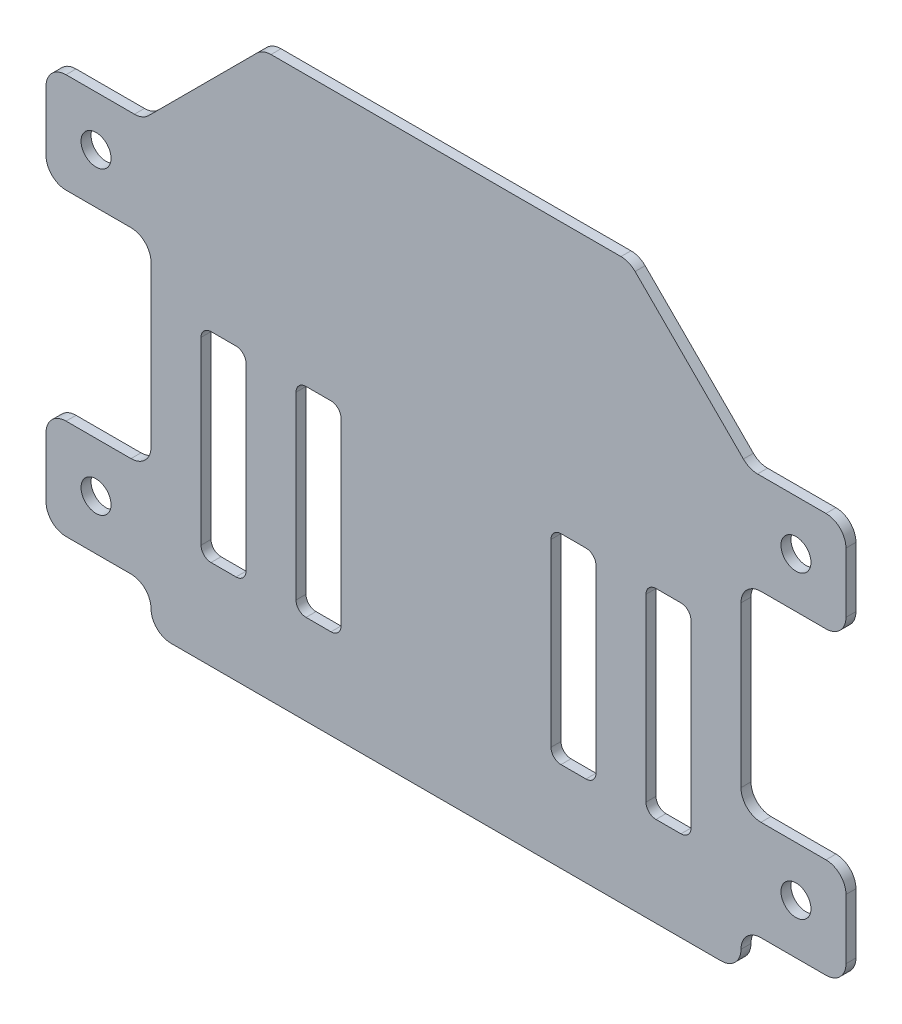
SolidWorks part; units mm, degrees
ref_plane "Спереди" through (0, 0, 0) normal (0, 0, 1) x (1, 0, 0)
ref_plane "Сверху" through (0, 0, 0) normal (0, 1, 0) x (1, 0, 0)
ref_plane "Справа" through (0, 0, 0) normal (1, 0, 0) x (0, 0, -1)
sketch "Model" plane through (0, 0, 0) normal (0, 0, 1) x (1, 0, 0)
  line L0 (-23.5, 9) -> (-21, 9)
  line L1 (-23.5, 29) -> (-21, 29)
  line L2 (-20, 28) -> (-20, 10)
  line L3 (-24.5, 10) -> (-24.5, 28)
  line L4 (-29.5, 16) -> (-29.5, 32)
  line L5 (-18.9142, 55.4142) -> (-29.7426, 44.5858)
  line L6 (-17.5, 56) -> (0, 56)
  line L7 (-38, 4) -> (-31.5, 4)
  line L8 (-38, 14) -> (-31.5, 14)
  line L9 (-40, 6) -> (-40, 12)
  line L10 (-14, 9) -> (-11.5, 9)
  line L11 (-14, 29) -> (-11.5, 29)
  line L12 (-10.5, 28) -> (-10.5, 10)
  line L13 (-15, 10) -> (-15, 28)
  line L14 (-38, 44) -> (-31.1569, 44)
  line L15 (-38, 34) -> (-31.5, 34)
  line L16 (-40, 42) -> (-40, 36)
  line L17 (-27.5, 0) -> (0, 0)
  line L18 (23.5, 9) -> (21, 9)
  line L19 (23.5, 29) -> (21, 29)
  line L20 (20, 28) -> (20, 10)
  line L21 (24.5, 10) -> (24.5, 28)
  line L22 (29.5, 16) -> (29.5, 32)
  line L23 (18.9142, 55.4142) -> (29.7426, 44.5858)
  line L24 (17.5, 56) -> (0, 56)
  line L25 (38, 4) -> (31.5, 4)
  line L26 (38, 14) -> (31.5, 14)
  line L27 (40, 6) -> (40, 12)
  line L28 (14, 9) -> (11.5, 9)
  line L29 (14, 29) -> (11.5, 29)
  line L30 (10.5, 28) -> (10.5, 10)
  line L31 (15, 10) -> (15, 28)
  line L32 (38, 44) -> (31.1569, 44)
  line L33 (38, 34) -> (31.5, 34)
  line L34 (40, 42) -> (40, 36)
  line L35 (27.5, 0) -> (0, 0)
  line L36 (23.5, 9) -> (21, 9)
  line L37 (23.5, 29) -> (21, 29)
  line L38 (20, 28) -> (20, 10)
  line L39 (24.5, 10) -> (24.5, 28)
  line L40 (29.5, 16) -> (29.5, 32)
  line L41 (18.9142, 55.4142) -> (29.7426, 44.5858)
  line L42 (17.5, 56) -> (0, 56)
  line L43 (38, 4) -> (31.5, 4)
  line L44 (38, 14) -> (31.5, 14)
  line L45 (40, 6) -> (40, 12)
  line L46 (14, 9) -> (11.5, 9)
  line L47 (14, 29) -> (11.5, 29)
  line L48 (10.5, 28) -> (10.5, 10)
  line L49 (15, 10) -> (15, 28)
  line L50 (38, 44) -> (31.1569, 44)
  line L51 (38, 34) -> (31.5, 34)
  line L52 (40, 42) -> (40, 36)
  line L53 (27.5, 0) -> (0, 0)
  circle A0 centre (-35, 9) radius 1.5
  arc A1 (-24.5, 10) -> (-23.5, 9) centre (-23.5, 10) ccw
  arc A2 (-21, 9) -> (-20, 10) centre (-21, 10) ccw
  arc A3 (-23.5, 29) -> (-24.5, 28) centre (-23.5, 28) ccw
  arc A4 (-20, 28) -> (-21, 29) centre (-21, 28) ccw
  circle A5 centre (-35, 9) radius 1.5
  arc A6 (-38, 14) -> (-40, 12) centre (-38, 12) ccw
  arc A7 (-40, 6) -> (-38, 4) centre (-38, 6) ccw
  arc A8 (-29.5, 2) -> (-31.5, 4) centre (-31.5, 2) ccw
  arc A9 (-31.5, 14) -> (-29.5, 16) centre (-31.5, 16) ccw
  arc A10 (-15, 10) -> (-14, 9) centre (-14, 10) ccw
  arc A11 (-11.5, 9) -> (-10.5, 10) centre (-11.5, 10) ccw
  arc A12 (-14, 29) -> (-15, 28) centre (-14, 28) ccw
  arc A13 (-10.5, 28) -> (-11.5, 29) centre (-11.5, 28) ccw
  circle A14 centre (-35, 39) radius 1.5
  circle A15 centre (-35, 39) radius 1.5
  arc A16 (-40, 36) -> (-38, 34) centre (-38, 36) ccw
  arc A17 (-38, 44) -> (-40, 42) centre (-38, 42) ccw
  arc A18 (-29.5, 32) -> (-31.5, 34) centre (-31.5, 32) ccw
  arc A19 (-29.5, 2) -> (-27.5, 0) centre (-27.5, 2) ccw
  arc A20 (-31.1569, 44) -> (-29.7426, 44.5858) centre (-31.1569, 46) ccw
  arc A21 (-17.5, 56) -> (-18.9142, 55.4142) centre (-17.5, 54) ccw
  circle A22 centre (35, 9) radius 1.5
  arc A23 (23.5, 9) -> (24.5, 10) centre (23.5, 10) ccw
  arc A24 (20, 10) -> (21, 9) centre (21, 10) ccw
  arc A25 (24.5, 28) -> (23.5, 29) centre (23.5, 28) ccw
  arc A26 (21, 29) -> (20, 28) centre (21, 28) ccw
  circle A27 centre (35, 9) radius 1.5
  arc A28 (40, 12) -> (38, 14) centre (38, 12) ccw
  arc A29 (38, 4) -> (40, 6) centre (38, 6) ccw
  arc A30 (31.5, 4) -> (29.5, 2) centre (31.5, 2) ccw
  arc A31 (29.5, 16) -> (31.5, 14) centre (31.5, 16) ccw
  arc A32 (14, 9) -> (15, 10) centre (14, 10) ccw
  arc A33 (10.5, 10) -> (11.5, 9) centre (11.5, 10) ccw
  arc A34 (15, 28) -> (14, 29) centre (14, 28) ccw
  arc A35 (11.5, 29) -> (10.5, 28) centre (11.5, 28) ccw
  circle A36 centre (35, 39) radius 1.5
  circle A37 centre (35, 39) radius 1.5
  arc A38 (38, 34) -> (40, 36) centre (38, 36) ccw
  arc A39 (40, 42) -> (38, 44) centre (38, 42) ccw
  arc A40 (31.5, 34) -> (29.5, 32) centre (31.5, 32) ccw
  arc A41 (27.5, 0) -> (29.5, 2) centre (27.5, 2) ccw
  arc A42 (29.7426, 44.5858) -> (31.1569, 44) centre (31.1569, 46) ccw
  arc A43 (18.9142, 55.4142) -> (17.5, 56) centre (17.5, 54) ccw
  circle A44 centre (35, 9) radius 1.5
  arc A45 (23.5, 9) -> (24.5, 10) centre (23.5, 10) ccw
  arc A46 (20, 10) -> (21, 9) centre (21, 10) ccw
  arc A47 (24.5, 28) -> (23.5, 29) centre (23.5, 28) ccw
  arc A48 (21, 29) -> (20, 28) centre (21, 28) ccw
  circle A49 centre (35, 9) radius 1.5
  arc A50 (40, 12) -> (38, 14) centre (38, 12) ccw
  arc A51 (38, 4) -> (40, 6) centre (38, 6) ccw
  arc A52 (31.5, 4) -> (29.5, 2) centre (31.5, 2) ccw
  arc A53 (29.5, 16) -> (31.5, 14) centre (31.5, 16) ccw
  arc A54 (14, 9) -> (15, 10) centre (14, 10) ccw
  arc A55 (10.5, 10) -> (11.5, 9) centre (11.5, 10) ccw
  arc A56 (15, 28) -> (14, 29) centre (14, 28) ccw
  arc A57 (11.5, 29) -> (10.5, 28) centre (11.5, 28) ccw
  circle A58 centre (35, 39) radius 1.5
  circle A59 centre (35, 39) radius 1.5
  arc A60 (38, 34) -> (40, 36) centre (38, 36) ccw
  arc A61 (40, 42) -> (38, 44) centre (38, 42) ccw
  arc A62 (31.5, 34) -> (29.5, 32) centre (31.5, 32) ccw
  arc A63 (27.5, 0) -> (29.5, 2) centre (27.5, 2) ccw
  arc A64 (29.7426, 44.5858) -> (31.1569, 44) centre (31.1569, 46) ccw
  arc A65 (18.9142, 55.4142) -> (17.5, 56) centre (17.5, 54) ccw
extrude "Бобышка-Вытянуть1" add sketch "Model" along normal blind 1 contours L23 A43 L24 L6 A21 L5 A20 L14 A17 L16 A16 L15 A18 L4 A9 L8 A6 L9 A7 L7 A8 A19 L17 L35 A41 A30 L25 A29 L27 A28 L26 A31 L22 A40 L33 A38 L34 A39 L32 A42 A0 A4 L2 A2 L0 A1 L3 A3 L1
